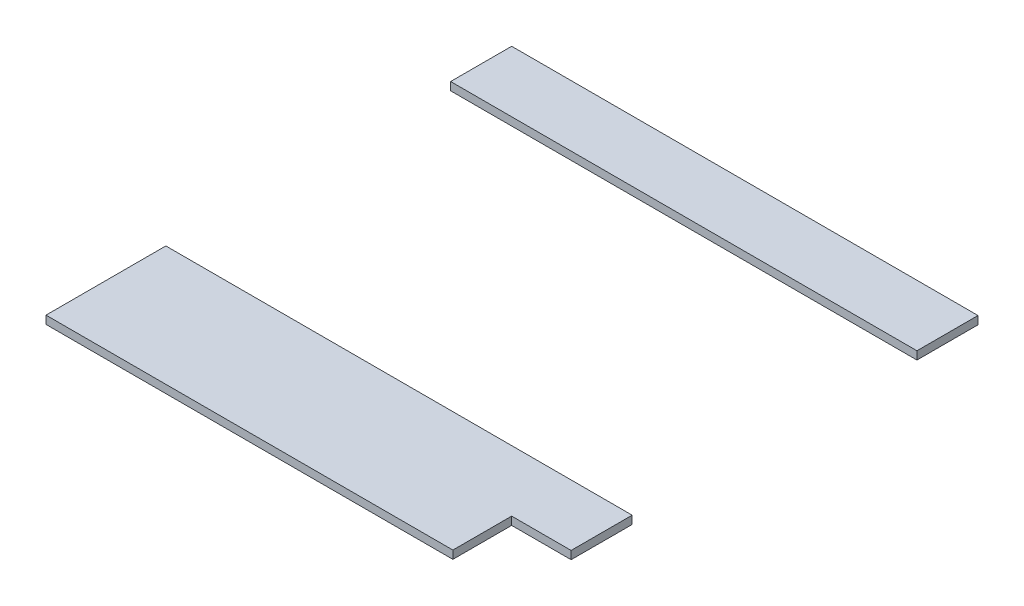
SolidWorks part; units mm, degrees
ref_plane "Front Plane" through (0, 0, 0) normal (0, 0, 1) x (1, 0, 0)
ref_plane "Top Plane" through (0, 0, 0) normal (0, 1, 0) x (1, 0, 0)
ref_plane "Right Plane" through (0, 0, 0) normal (1, 0, 0) x (0, 0, -1)
sketch "Sketch1" plane through (0, 0, 0) normal (0, 1, 0) x (1, 0, 0)
  line L0 (0, 0) -> (-35, 0) construction
  line L1 (-80.6396, -56.4396) -> (104.2, -56.4396) construction
  line L2 (104.2, -80.6396) -> (104.2, -56.4396) construction
  line L3 (-80.6396, -80.6396) -> (104.2, -80.6396) construction
  line L5 (104.2, 56.4396) -> (-80.6396, 56.4396) construction
  line L6 (-80.6396, 56.4396) -> (-80.6396, 80.6396) construction
  line L7 (-80.6396, 80.6396) -> (104.2, 80.6396) construction
  line L8 (104.2, 80.6396) -> (104.2, 56.4396) construction
  line L9 (-80.6396, -56.4396) -> (104.2, -56.4396)
  line L10 (104.2, -80.6396) -> (104.2, -56.4396)
  line L11 (80.6396, -80.6396) -> (104.2, -80.6396)
  line L13 (104.2, 56.4396) -> (-80.6396, 56.4396)
  line L14 (-80.6396, 56.4396) -> (-80.6396, 80.6396)
  line L15 (-80.6396, 80.6396) -> (104.2, 80.6396)
  line L16 (104.2, 80.6396) -> (104.2, 56.4396)
  line L17 (80.6396, -103.9396) -> (80.6396, -80.6396) construction
  line L18 (-80.6396, -103.9396) -> (80.6396, -103.9396) construction
  line L19 (80.6396, -103.9396) -> (80.6396, -80.6396)
  line L20 (-80.6396, -103.9396) -> (80.6396, -103.9396)
  line L21 (-80.6396, -103.9396) -> (-80.6396, -56.4396)
  line L22 (80.6396, -80.6396) -> (-80.6396, -80.6396) construction
  circle A0 centre (0, 0) radius 35 construction
  circle A1 centre (0, 0) radius 35 construction
extrude "Boss-Extrude1" add sketch "Sketch1" against normal up to vertex (3.2 mm away)
